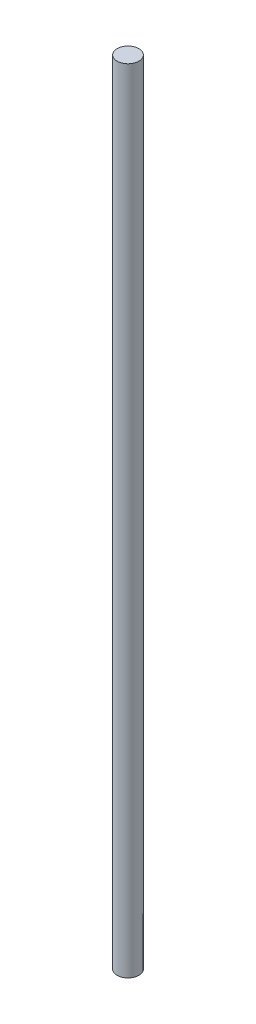
SolidWorks part; units mm, degrees
material "普通碳钢"
ref_plane "前视基准面" through (0, 0, 0) normal (0, 0, 1) x (1, 0, 0)
ref_plane "上视基准面" through (0, 0, 0) normal (0, 1, 0) x (1, 0, 0)
ref_plane "右视基准面" through (0, 0, 0) normal (1, 0, 0) x (0, 0, -1)
other "Configuration Table"
sketch "草图1" plane through (0, 0, 0) normal (0, 1, 0) x (1, 0, 0)
  circle A0 centre (0, 0) radius 2.75
  dimension "D1" = 5.5
extrude "凸台-拉伸1" add sketch "草图1" along normal blind 200
